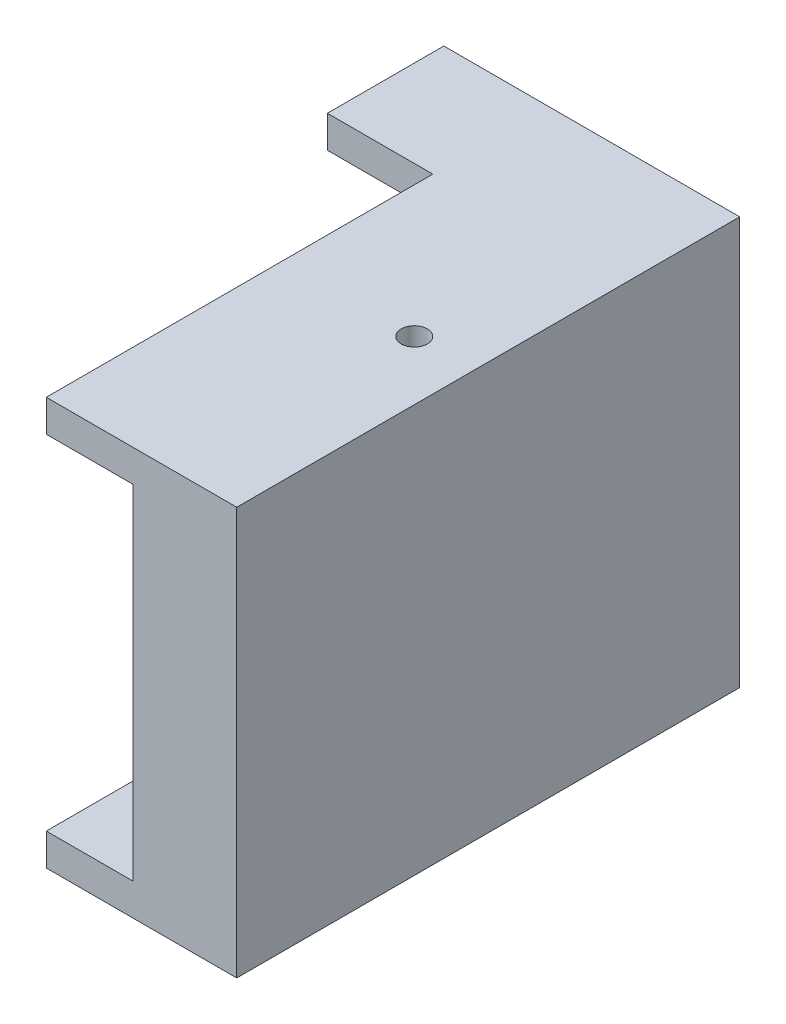
SolidWorks part; units mm, degrees
material "ABS"
ref_plane "Front Plane" through (0, 0, 0) normal (0, 0, 1) x (1, 0, 0)
ref_plane "Top Plane" through (0, 0, 0) normal (0, 1, 0) x (1, 0, 0)
ref_plane "Right Plane" through (0, 0, 0) normal (1, 0, 0) x (0, 0, -1)
sketch "Sketch1" plane through (0, 0, 0) normal (0, 1, 0) x (1, 0, 0)
  line L0 (-50.8, -20) -> (-32.7, -20)
  line L1 (-32.7, -20) -> (-32.7, -86.36)
  line L2 (-32.7, -86.36) -> (0, -86.36)
  line L3 (0, -86.36) -> (0, 0)
  line L4 (0, 0) -> (-50.8, 0)
  line L5 (-50.8, 0) -> (-50.8, -20)
  point P6 (0, 0)
  dimension "D1" = 18.1
  dimension "D2" = 20
  dimension "D3" = 50.8
  dimension "D4" = 86.36
extrude "Boss-Extrude1" add sketch "Sketch1" along normal blind 70
sketch "Sketch2" plane through (-50.8, 0, 0) normal (-1, 0, 0) x (0, 0, 1)
  line L0 (86.36, 70) -> (86.36, 0) construction
  line L1 (86.36, 64.5) -> (7.36, 64.5)
  line L2 (86.36, 64.5) -> (86.36, 5.5)
  line L3 (86.36, 5.5) -> (7.36, 5.5)
  line L4 (7.36, 64.5) -> (7.36, 5.5)
  line L5 (0, 70) -> (0, 0) construction
  line L6 (0, 35) -> (86.36, 35) construction
  dimension "D1" = 59
  dimension "D2" = 79
extrude "Cut-Extrude1" cut sketch "Sketch2" against normal blind 33.02
sketch "Sketch3" plane through (0, 70, 0) normal (0, 1, 0) x (1, 0, 0)
  line L0 (0, 0) -> (-50.8, 0) construction
  line L1 (-50.8, 0) -> (-50.8, -20) construction
  circle A0 centre (-10.16, -45.72) radius 2.2479
  dimension "D1" = 4.4958
  dimension "D2" = 45.72
  dimension "D3" = 40.64
extrude "Cut-Extrude2" cut sketch "Sketch3" against normal through all
